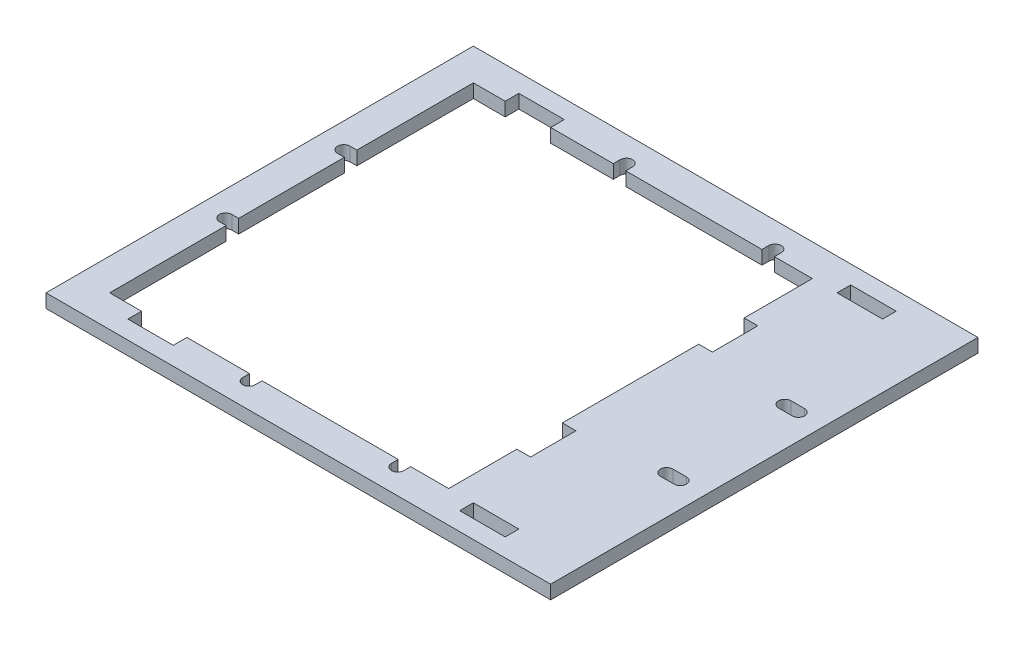
SolidWorks part; units mm, degrees
ref_plane "Front" through (0, 0, 0) normal (0, 0, 1) x (1, 0, 0)
ref_plane "Top" through (0, 0, 0) normal (0, 1, 0) x (1, 0, 0)
ref_plane "Right" through (0, 0, 0) normal (1, 0, 0) x (0, 0, -1)
sketch "Croquis1" plane through (0, 0, 0) normal (0, 1, 0) x (1, 0, 0)
  line L5 (-7, -7) -> (-7, 87)
  line L6 (0, 0) -> (30.7751, 0)
  line L10 (0, 0) -> (0, 80)
  line L11 (0, 80) -> (30.7751, 80)
  line L13 (0, 0) -> (104, 85.7732) construction
  line L14 (0, 80) -> (104, -5.7732) construction
  line L15 (-7, 87) -> (104, 87)
  line L16 (104, -7) -> (104, 87)
  line L17 (-7, -7) -> (104, -7)
  line L18 (74.57, 80) -> (74.57, 65)
  line L19 (0, 0) -> (97, 0) construction
  line L20 (0, 80) -> (97, 80) construction
  line L21 (-7, 40) -> (104, 40) construction
  line L22 (0, 80) -> (-1.5, 80) construction
  line L23 (97, 0) -> (97, 80) construction
  line L24 (-1.5, 54.375) -> (0, 54.375)
  line L25 (-1.5, 51.625) -> (0, 51.625)
  line L26 (-1.5, 28.375) -> (0, 28.375)
  line L27 (-1.5, 25.625) -> (0, 25.625)
  line L28 (74.57, 0) -> (97, 0) construction
  line L29 (97, 0) -> (97, 80) construction
  line L30 (97, 80) -> (74.57, 80) construction
  line L31 (48.5, 40) -> (48.5, 87) construction
  line L32 (98.5, 25.625) -> (95.5, 25.625)
  line L33 (98.5, 28.375) -> (95.5, 28.375)
  line L34 (98.5, 51.625) -> (95.5, 51.625)
  line L35 (98.5, 54.375) -> (95.5, 54.375)
  line L36 (33.525, 81.5) -> (33.525, 80)
  line L37 (30.775, 81.4999) -> (30.7751, 80)
  line L38 (33.525, 80) -> (63.475, 80)
  line L41 (66.225, 80) -> (74.57, 80)
  line L42 (66.225, -1.5) -> (66.225, 0)
  line L44 (33.525, 0) -> (63.475, 0)
  line L45 (30.775, -1.4999) -> (30.7751, 0)
  line L46 (33.525, -1.5) -> (33.525, 0)
  line L48 (66.225, 0) -> (74.57, 0)
  line L49 (7, -3) -> (17, 0) construction
  line L50 (7, 80) -> (17, 80)
  line L51 (7, 80) -> (7, 83)
  line L52 (7, 83) -> (17, 83)
  line L53 (17, 80) -> (17, 83)
  line L54 (7, 80) -> (17, 83) construction
  line L55 (7, 83) -> (17, 80) construction
  line L56 (7, 0) -> (17, -3) construction
  line L57 (17, 0) -> (17, -3)
  line L58 (7, -3) -> (17, -3)
  line L59 (7, 0) -> (7, -3)
  line L60 (7, 0) -> (17, 0)
  line L61 (90, -3) -> (80, 0) construction
  line L62 (90, 80) -> (80, 80)
  line L63 (90, 80) -> (90, 83)
  line L64 (90, 83) -> (80, 83)
  line L65 (80, 80) -> (80, 83)
  line L66 (90, 80) -> (80, 83) construction
  line L67 (90, 83) -> (80, 80) construction
  line L68 (90, 0) -> (80, -3) construction
  line L69 (80, 0) -> (80, -3)
  line L70 (90, -3) -> (80, -3)
  line L71 (90, 0) -> (90, -3)
  line L72 (90, 0) -> (80, 0)
  line L73 (63.475, 81.5001) -> (66.225, 81.5) construction
  line L74 (63.475, -1.5001) -> (63.475, 0)
  line L75 (63.475, -1.5001) -> (66.225, -1.5) construction
  line L76 (63.475, 81.5001) -> (63.475, 80)
  line L77 (66.225, 81.5) -> (66.225, 80)
  line L78 (66.225, 80) -> (66.4751, 80)
  line L79 (74.57, 55) -> (74.57, 0)
  line L80 (74.57, 65) -> (77.57, 65)
  line L82 (74.57, 55) -> (77.57, 55)
  line L83 (77.57, 65) -> (77.57, 55)
  line L84 (74.57, 65) -> (77.57, 55) construction
  line L85 (74.57, 55) -> (77.57, 65) construction
  line L86 (74.57, 25) -> (77.57, 15) construction
  line L87 (74.57, 15) -> (77.57, 25) construction
  line L88 (77.57, 15) -> (77.57, 25)
  line L89 (74.57, 25) -> (77.57, 25)
  line L90 (74.57, 15) -> (77.57, 15)
  arc A0 (-1.5, 54.375) -> (-1.5, 51.625) centre (-1.5, 53) ccw
  arc A2 (-1.5, 25.625) -> (-1.5, 28.375) centre (-1.5, 27) cw
  arc A3 (98.5, 25.625) -> (98.5, 28.375) centre (98.5, 27) ccw
  arc A4 (98.5, 54.375) -> (98.5, 51.625) centre (98.5, 53) cw
  arc A5 (95.5, 54.375) -> (95.5, 51.625) centre (95.5, 53) ccw
  arc A6 (95.5, 25.625) -> (95.5, 28.375) centre (95.5, 27) cw
  arc A7 (33.525, 81.5) -> (30.775, 81.4999) centre (32.15, 81.5) ccw
  arc A10 (33.525, -1.5) -> (30.775, -1.4999) centre (32.15, -1.5) cw
  arc A11 (63.475, -1.5001) -> (66.225, -1.5) centre (64.85, -1.5) ccw
  arc A12 (63.475, 81.5001) -> (66.225, 81.5) centre (64.85, 81.5) cw
  point P4 (48.5, 40)
  point P41 (97, 25.625)
  point P42 (97, 28.375)
  point P43 (97, 51.625)
  point P50 (97, 54.375)
  point P74 (12, 81.5)
  point P79 (12, -1.5)
  point P83 (85, 81.5)
  point P88 (85, -1.5)
  point P93 (76.07, 60)
  point P98 (76.07, 20)
  dimension "D1" = 2.75
  dimension "D7" = 2.75
  dimension "D2" = 80
  dimension "D3" = 7
  dimension "D4" = 74.57
  dimension "D5" = 1.5
  dimension "D6" = 13
  dimension "D8" = 1.5
  dimension "D9" = 32.15
  dimension "D10" = 2.75
  dimension "D11" = 10
  dimension "D12" = 7
  dimension "D13" = 3
  dimension "D14" = 3
  dimension "D15" = 10
  dimension "D16" = 7
  dimension "D17" = 32.7
  dimension "D18" = 3
  dimension "D19" = 15
  dimension "D20" = 10
extrude "Saliente-Extruir1" add sketch "Croquis1" along normal blind 3
